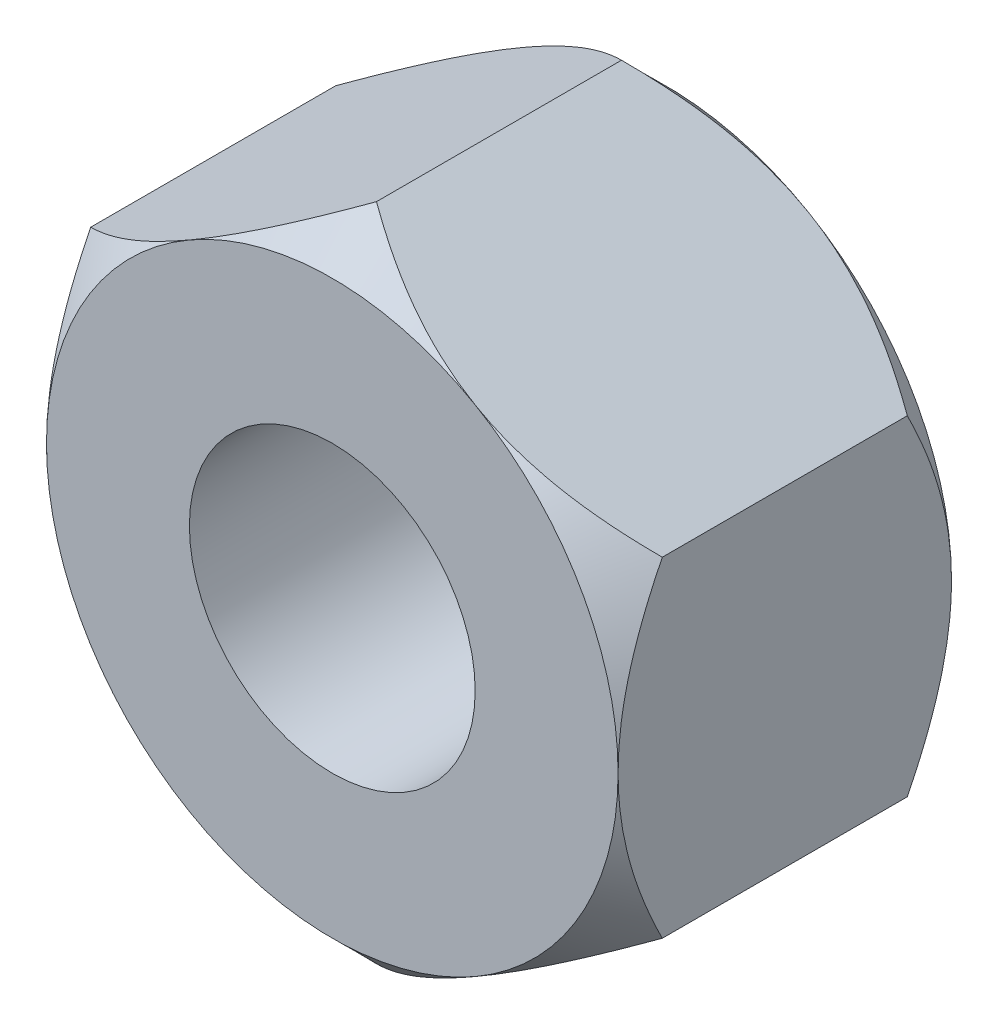
SolidWorks part; units mm, degrees
ref_plane "Front Plane" through (0, 0, 0) normal (0, 0, 1) x (1, 0, 0)
ref_plane "Top Plane" through (0, 0, 0) normal (0, 1, 0) x (1, 0, 0)
ref_plane "Right Plane" through (0, 0, 0) normal (1, 0, 0) x (0, 0, -1)
sketch "Sketch1" plane through (0, 0, 0) normal (0, 0, 1) x (1, 0, 0)
  line L1 (0, -3.4641) -> (3, -1.7321)
  line L2 (3, -1.7321) -> (3, 1.7321)
  line L3 (3, 1.7321) -> (0, 3.4641)
  line L4 (0, 3.4641) -> (-3, 1.7321)
  line L5 (-3, 1.7321) -> (-3, -1.7321)
  line L6 (-3, -1.7321) -> (0, -3.4641)
  circle A0 centre (0, 0) radius 3 construction
  circle A1 centre (0, 0) radius 1.5
  dimension "D1" = 3
  dimension "D2" = 6
extrude "Boss-Extrude1" add sketch "Sketch1" along normal blind 3.5
sketch "Sketch2" plane through (0, 0, 3.5) normal (0, 0, 1) x (1, 0, 0)
  line L0 (0, 3.4641) -> (-3, 1.7321) construction
  circle A0 centre (0, 0) radius 3
extrude "Cut-Extrude2" cut sketch "Sketch2" against normal through all draft 45 flip side to cut
ref_plane "Plane1" through (0, 0, 1.75) normal (0, 0, -1) x (-1, 0, 0)
mirror "Mirror1" about plane through (0, 0, 1.75) normal (0, 0, -1) of "Cut-Extrude2"
